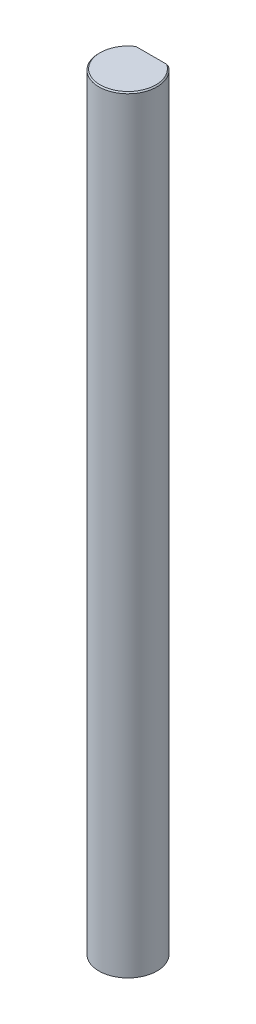
SolidWorks part; units mm, degrees
ref_plane "前视基准面" through (0, 0, 0) normal (0, 0, 1) x (1, 0, 0)
ref_plane "上视基准面" through (0, 0, 0) normal (0, 1, 0) x (1, 0, 0)
ref_plane "右视基准面" through (0, 0, 0) normal (1, 0, 0) x (0, 0, -1)
sketch "草图1" plane through (0, 0, 0) normal (0, 1, 0) x (1, 0, 0)
  circle A0 centre (0, 0) radius 2.5
extrude "凸台-拉伸1" add sketch "草图1" along normal blind 66
sketch3d "3D草图1"
  point P0 (0.0689, 66, -0.2516)
ref_plane "基准面4" through (0, 66, 0) normal (0, 1, 0) x (1, 0, 0)
sketch "草图2" plane through (0, 66, 0) normal (0, 1, 0) x (1, 0, 0)
  line L2 (-1.5, 2) -> (1.5, 2)
  circle A0 centre (0, 0) radius 2.5 construction
  arc A1 (1.5, 2) -> (-1.5, 2) centre (0, 0) ccw
chamfer "倒角1" distance 0.1 angle 45 1 edges at (0, 66, 2.5)
extrude "切除-拉伸2" cut sketch "草图2" against normal blind 18 contours A1 L2
